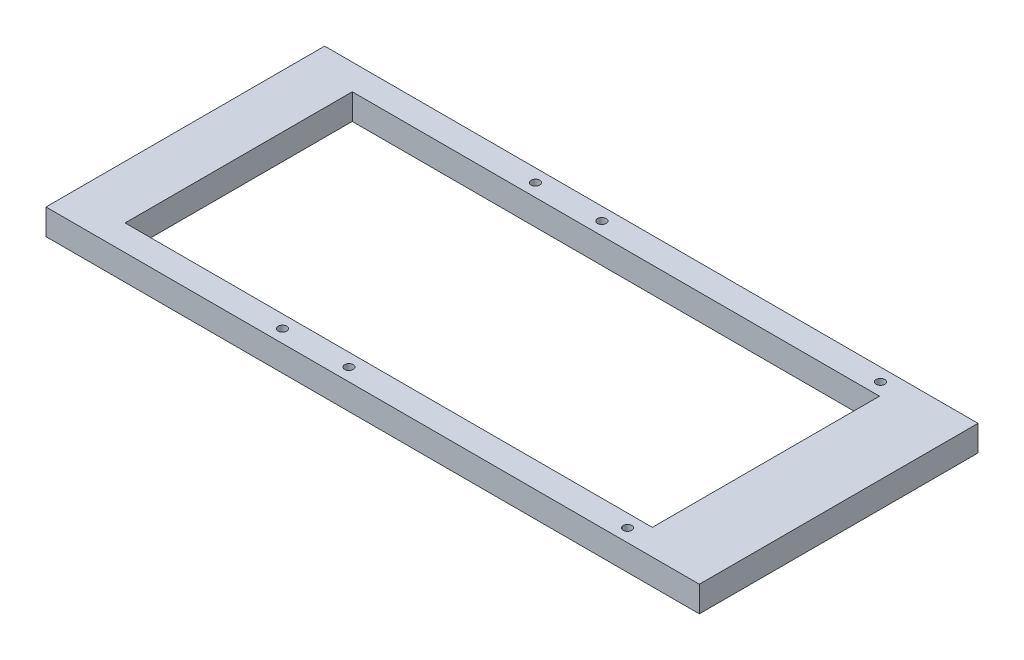
SolidWorks part; units mm, degrees
material "1060 Alloy"
ref_plane "Front Plane" through (0, 0, 0) normal (0, 0, 1) x (1, 0, 0)
ref_plane "Top Plane" through (0, 0, 0) normal (0, 1, 0) x (1, 0, 0)
ref_plane "Right Plane" through (0, 0, 0) normal (1, 0, 0) x (0, 0, -1)
sketch "Sketch1" plane through (0, 0, 0) normal (0, 1, 0) x (1, 0, 0)
  line L0 (110.0769, -53) -> (135, -65) construction
  line L1 (-135, 65) -> (135, 65)
  line L3 (-135, -65) -> (135, -65)
  line L4 (135, 65) -> (135, -65)
  line L5 (-135, 65) -> (-110.0769, 53) construction
  line L6 (-135, -65) -> (-110.0769, -53) construction
  line L7 (-144.9474, 53) -> (101.0526, 53)
  line L8 (-144.9474, 53) -> (-144.9474, -53)
  line L9 (-144.9474, -53) -> (101.0526, -53)
  line L10 (101.0526, 53) -> (101.0526, -53)
  line L11 (-135, -65) -> (-169.8404, -65)
  line L12 (-169.8404, -65) -> (-169.8404, 65)
  line L13 (110.0769, 53) -> (135, 65) construction
  line L14 (-169.8404, 65) -> (-135, 65)
  point P0 (0, 0)
  point P6 (0, 0)
  dimension "D1" = 270
  dimension "D2" = 130
  dimension "D3" = 106
  dimension "D4" = 246
extrude "Boss-Extrude1" add sketch "Sketch1" along normal blind 12
sketch "Sketch3" plane through (0, 12, 0) normal (0, 1, 0) x (1, 0, 0)
  line L0 (-169.8404, -65) -> (135, -65) construction
  line L2 (-135, 65) -> (-135, -65) construction
  circle A0 centre (-65.5, -59) radius 2
  dimension "D3" = 4
  dimension "D1" = 6
  dimension "D2" = 69.5
extrude "Cut-Extrude1" cut sketch "Sketch3" against normal blind 50.25
mirror "Mirror1" about plane through (0, 0, 0) normal (0, 0, 1) of "Cut-Extrude1"
pattern_linear "LPattern1" count 2 spacing 31 along (1, 0, 0) of "Mirror1", "Cut-Extrude1"
pattern_linear "LPattern2" count 2 spacing 161 along (1, 0, 0) of "Cut-Extrude1"
mirror "Mirror2" about plane through (0, 0, 0) normal (0, 0, 1) of "LPattern2"
